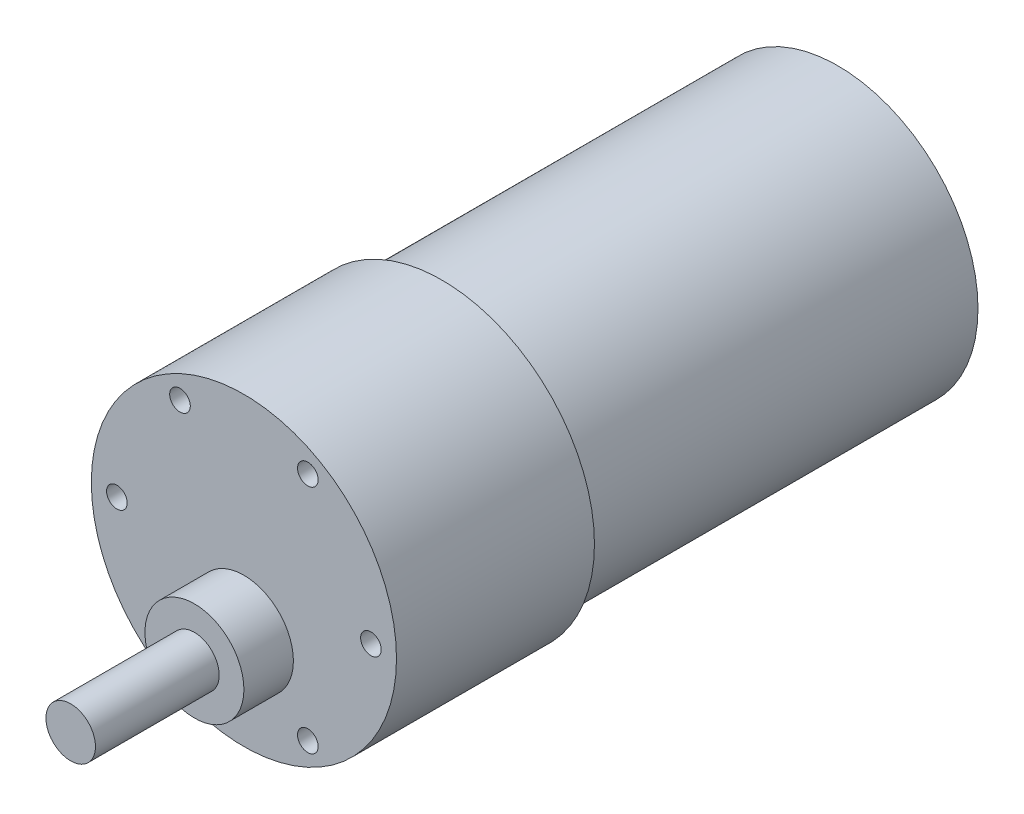
SolidWorks part; units mm, degrees
ref_plane "Alzado" through (0, 0, 0) normal (0, 0, 1) x (1, 0, 0)
ref_plane "Planta" through (0, 0, 0) normal (0, 1, 0) x (1, 0, 0)
ref_plane "Vista lateral" through (0, 0, 0) normal (1, 0, 0) x (0, 0, -1)
sketch "Croquis1" plane through (0, 0, 0) normal (0, 0, 1) x (1, 0, 0)
  circle A0 centre (0, 0) radius 17
  dimension "D1" = 34
extrude "Saliente-Extruir1" add sketch "Croquis1" along normal blind 48
sketch "Croquis2" plane through (0, 0, 48) normal (0, 0, 1) x (1, 0, 0)
  circle A0 centre (0, 0) radius 18.5
  dimension "D1" = 37
extrude "Saliente-Extruir2" add sketch "Croquis2" along normal blind 24
sketch "Croquis3" plane through (0, 0, 72) normal (0, 0, 1) x (1, 0, 0)
  circle A0 centre (0, -6.5) radius 6
  circle A1 centre (0, 0) radius 18.5 construction
  dimension "D1" = 12
  dimension "D2" = 6.5
  dimension "D3" = 0
extrude "Saliente-Extruir3" add sketch "Croquis3" along normal blind 6
sketch "Croquis4" plane through (0, 0, 78) normal (0, 0, 1) x (1, 0, 0)
  circle A0 centre (0, -6.5) radius 3
  dimension "D1" = 6
extrude "Saliente-Extruir4" add sketch "Croquis4" along normal blind 15
sketch "Croquis5" plane through (0, 0, 72) normal (0, 0, 1) x (1, 0, 0)
  circle A0 centre (-7.75, -14) radius 1.25
  circle A1 centre (7.75, -14) radius 1.25
  circle A2 centre (-15.4, 0) radius 1.25
  circle A3 centre (15.4, 0) radius 1.25
  circle A5 centre (-7.75, 14) radius 1.25
  circle A6 centre (7.75, 14) radius 1.25
  circle A7 centre (0, 0) radius 18.5 construction
  dimension "D1" = 2.5
  dimension "D2" = 2.5
  dimension "D3" = 15.5
  dimension "D4" = 7.75
  dimension "D5" = 2.5
  dimension "D6" = 2.5
  dimension "D7" = 30.8
  dimension "D8" = 15.4
  dimension "D10" = 14
  dimension "D11" = 14
  dimension "D12" = 14
  dimension "D9" = 2
extrude "Cortar-Extruir3" cut sketch "Croquis5" against normal blind 14
